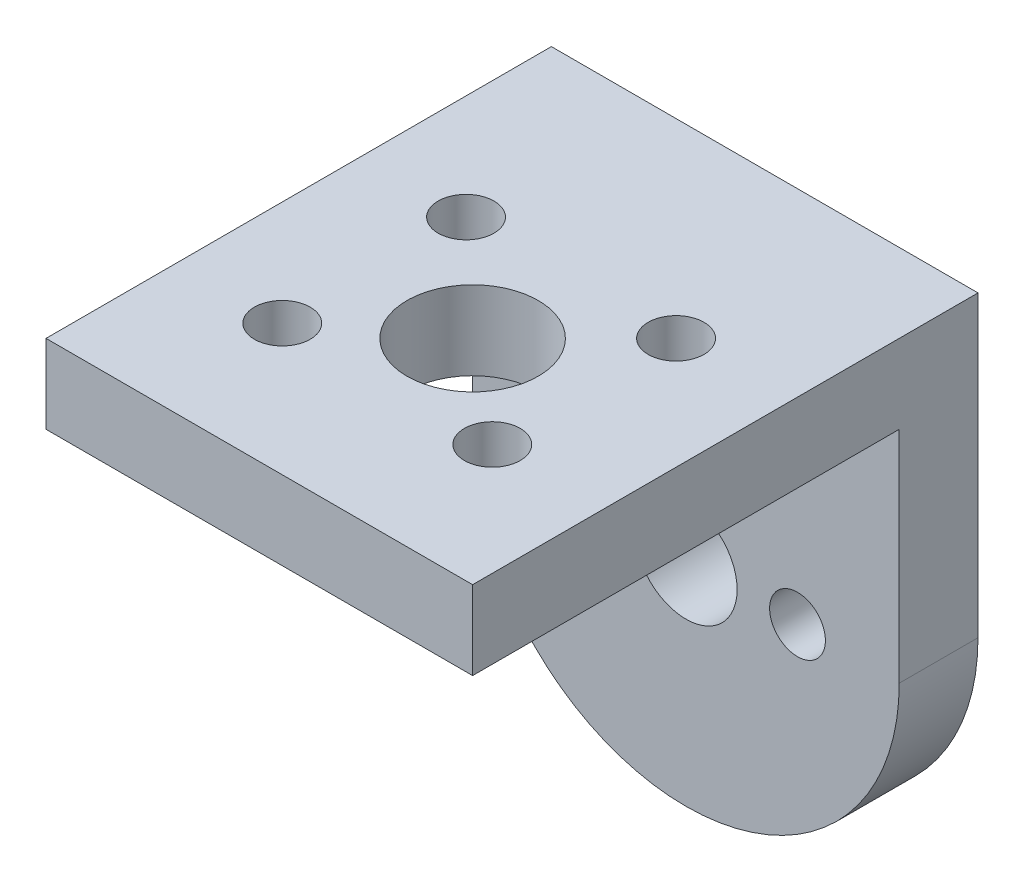
SolidWorks part; units mm, degrees
ref_plane "Front Plane" through (0, 0, 0) normal (0, 0, 1) x (1, 0, 0)
ref_plane "Top Plane" through (0, 0, 0) normal (0, 1, 0) x (1, 0, 0)
ref_plane "Right Plane" through (0, 0, 0) normal (1, 0, 0) x (0, 0, -1)
sketch "Sketch1" plane through (0, 0, 0) normal (0, 1, 0) x (1, 0, 0)
  line L0 (16.25, 32.5) -> (16.25, 0) construction
  line L1 (0, 0) -> (32.5, 0)
  line L2 (0, 0) -> (0, 32.5)
  line L3 (0, 32.5) -> (32.5, 32.5)
  line L4 (32.5, 0) -> (32.5, 32.5)
  circle A0 centre (24, 10) radius 2.125
  circle A1 centre (24, 24) radius 2.125
  circle A2 centre (8, 24) radius 2.125
  circle A3 centre (8, 10) radius 2.125
  circle A4 centre (16.25, 16.25) radius 5
  point P17 (16.25, 16.25)
  point P18 (0, 0)
  point P19 (0, 0)
  point P20 (0, 0)
  dimension "D6" = 4.25
  dimension "D7" = 4.25
  dimension "D8" = 4.25
  dimension "D9" = 4.25
  dimension "D12" = 10
  dimension "D1" = 32.5
  dimension "D2" = 32.5
  dimension "D3" = 16
  dimension "D4" = 16
  dimension "D5" = 14
  dimension "D10" = 10
  dimension "D11" = 8
extrude "Boss-Extrude1" add sketch "Sketch1" along normal blind 6
sketch "Sketch2" plane through (0, 6, 0) normal (0, 1, 0) x (1, 0, 0)
  line L1 (0, 32.5) -> (32.5, 32.5)
  line L2 (0, 32.5) -> (0, 38.5)
  line L3 (0, 38.5) -> (32.5, 38.5)
  line L4 (0, 32.5) -> (0, 0)
  line L5 (0, 0) -> (32.5, 0)
  line L6 (32.5, 0) -> (32.5, 32.5)
  line L7 (32.5, 32.5) -> (0, 32.5)
  line L8 (0, 32.5) -> (0, 0)
  line L9 (0, 0) -> (32.5, 0)
  line L10 (32.5, 0) -> (32.5, 32.5)
  line L11 (32.5, 32.5) -> (0, 32.5)
  line L12 (32.5, 32.5) -> (32.5, 38.5)
  line M9 (32.5, 32.5) -> (0, 32.5)
  dimension "D2" = 6
  dimension "D1" = 0
extrude "Boss-Extrude2" add sketch "Sketch2" against normal blind 39 contours L12 L3 L2 M9
sketch "Sketch3" plane through (0, 0, -32.5) normal (0, 0, 1) x (1, 0, 0)
  line L0 (16.25, 0) -> (16.25, -33) construction
  line L4 (32.5, -33) -> (32.5, 0)
  line L5 (32.5, 0) -> (0, 0)
  line L6 (0, 0) -> (0, -33)
  line L7 (0, -33) -> (32.5, -33)
  line L8 (32.5, -33) -> (32.5, 0)
  line L9 (32.5, 0) -> (0, 0)
  line L10 (0, 0) -> (0, -33)
  line L11 (0, -33) -> (32.5, -33)
  circle A0 centre (16.25, -16.75) radius 16.25
  line M6 (32.5, -33) -> (32.5, 0)
  line M9 (0, -33) -> (32.5, -33)
  dimension "D1" = 0
extrude "Cut-Extrude1" cut sketch "Sketch3" against normal blind 39 contours A0 L11 M6 | A0 L10 M9
sketch "Sketch4" plane through (0, 0, -32.5) normal (0, 0, 1) x (1, 0, 0)
  line L0 (0, -16.75) -> (32.5, -16.75) construction
  line L3 (0, 0) -> (0, -16.75)
  line L4 (32.5, -16.75) -> (32.5, 0)
  line L5 (32.5, 0) -> (0, 0)
  line L6 (0, 0) -> (0, -16.75)
  line L7 (32.5, -16.75) -> (32.5, 0)
  line L8 (32.5, 0) -> (0, 0)
  circle A0 centre (16.25, -16.75) radius 3.9
  arc A1 (0, -16.75) -> (32.5, -16.75) centre (16.25, -16.75) ccw
  arc A2 (0, -16.75) -> (32.5, -16.75) centre (16.25, -16.75) ccw
  circle A3 centre (7.75, -16.75) radius 2.125
  circle A4 centre (24.75, -16.75) radius 2.125
  dimension "D2" = 7.8
  dimension "D3" = 4.25
  dimension "D4" = 4.25
  dimension "D5" = 8.5
  dimension "D6" = 8.5
  dimension "D1" = 0
extrude "Cut-Extrude2" cut sketch "Sketch4" against normal blind 39 contours A0 | A4 | A3
